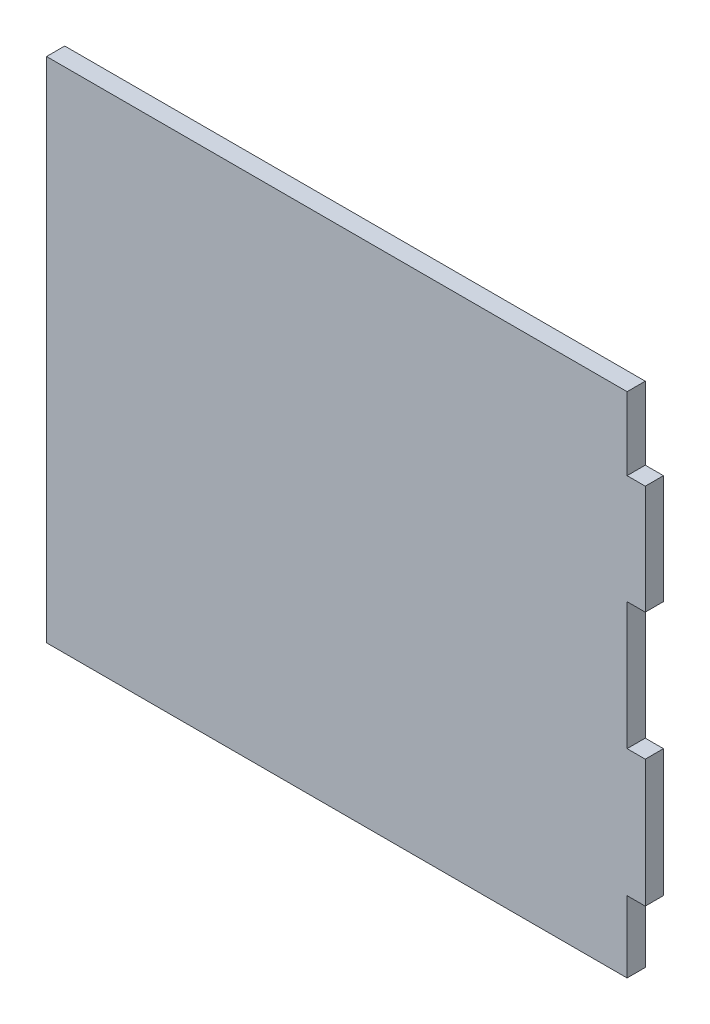
SolidWorks part; units mm, degrees
ref_plane "Front Plane" through (0, 0, 0) normal (0, 0, 1) x (1, 0, 0)
ref_plane "Top Plane" through (0, 0, 0) normal (0, 1, 0) x (1, 0, 0)
ref_plane "Right Plane" through (0, 0, 0) normal (1, 0, 0) x (0, 0, -1)
sketch "Model" plane through (0, 0, 0) normal (0, 0, 1) x (1, 0, 0)
  line L0 (-104.5285, 88.6534) -> (98.1784, 88.6534)
  line L1 (98.1784, 88.6534) -> (98.1784, 63.2534)
  line L2 (98.1784, 63.2534) -> (104.5284, 63.2534)
  line L3 (104.5284, 63.2534) -> (104.5284, 25.1534)
  line L4 (104.5284, 25.1534) -> (98.1784, 25.1534)
  line L5 (98.1784, 25.1534) -> (98.1784, -19.2966)
  line L6 (98.1784, -19.2966) -> (104.5284, -19.2966)
  line L7 (104.5284, -19.2966) -> (104.5284, -63.7465)
  line L8 (104.5284, -63.7465) -> (98.1784, -63.7465)
  line L9 (98.1784, -63.7465) -> (98.1784, -88.6533)
  line L10 (98.1784, -88.6533) -> (-104.5285, -88.6533)
  line L11 (-104.5285, -88.6533) -> (-104.5285, 88.6534)
extrude "Boss-Extrude1" add sketch "Model" along normal blind 6.35 contours L0 L1 L2 L3 L4 L5 L6 L7 L8 L9 L10 L11
